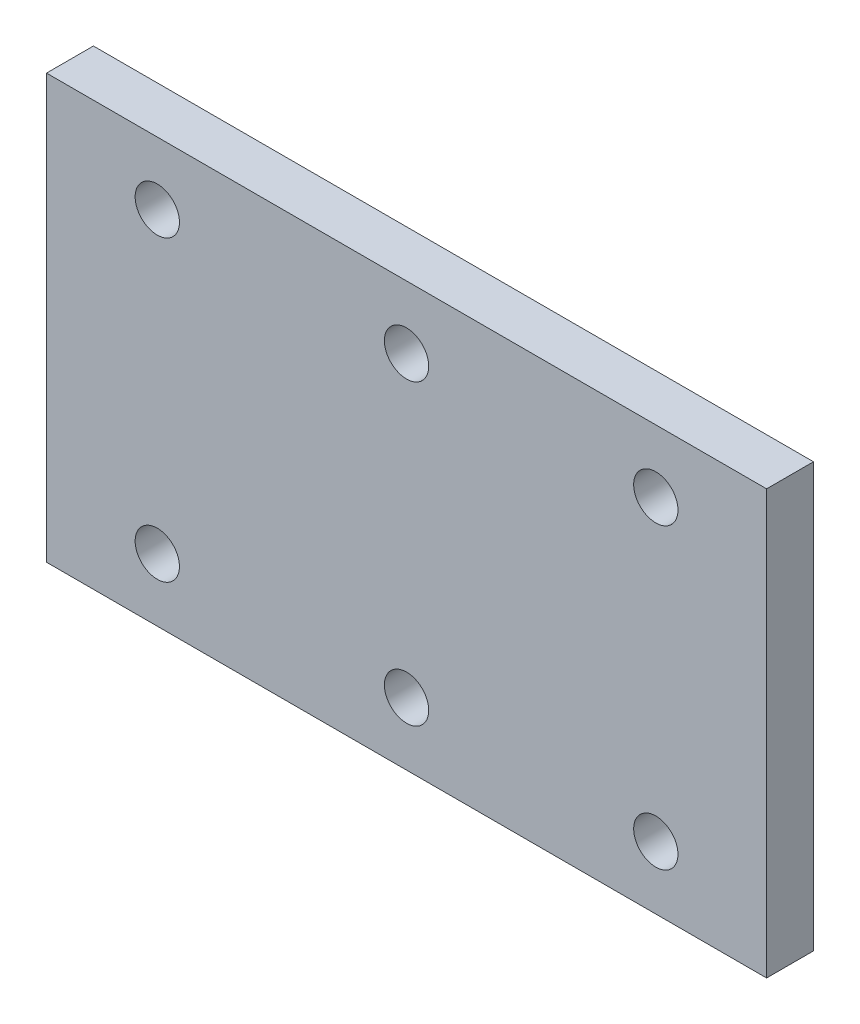
SolidWorks part; units mm, degrees
ref_plane "Front Plane" through (0, 0, 0) normal (0, 0, 1) x (1, 0, 0)
ref_plane "Top Plane" through (0, 0, 0) normal (0, 1, 0) x (1, 0, 0)
ref_plane "Right Plane" through (0, 0, 0) normal (1, 0, 0) x (0, 0, -1)
sketch "Sketch1" plane through (0, 0, 0) normal (0, 0, 1) x (1, 0, 0)
  line L1 (-48.75, 28.68) -> (48.75, 28.68)
  line L2 (-48.75, 28.68) -> (-48.75, -28.68)
  line L3 (-48.75, -28.68) -> (48.75, -28.68)
  line L4 (48.75, 28.68) -> (48.75, -28.68)
  line L5 (-48.75, 28.68) -> (48.75, -28.68) construction
  line L6 (-48.75, -28.68) -> (48.75, 28.68) construction
  point P0 (0, 0)
  dimension "D1" = 97.5
  dimension "D2" = 57.36
extrude "Boss-Extrude1" add sketch "Sketch1" along normal blind 6.35
sketch "Sketch2" plane through (0, 0, 6.35) normal (0, 0, 1) x (1, 0, 0)
  line L0 (-48.75, 28.68) -> (-48.75, -28.68) construction
  line L2 (48.75, 28.68) -> (-48.75, 28.68) construction
  line L3 (48.75, -28.68) -> (48.75, 28.68) construction
  line L5 (3.4925, 0) -> (-3.4925, 0) construction
  circle A0 centre (-33.75, 20.18) radius 3
  circle A1 centre (0, 20.18) radius 3
  circle A2 centre (33.75, 20.18) radius 3
  circle A6 centre (67.5, 20.18) radius 3 [skipped]
  circle A7 centre (101.25, 20.18) radius 3 [skipped]
  circle A8 centre (135, 20.18) radius 3 [skipped]
  circle A9 centre (33.75, -20.18) radius 3
  circle A10 centre (0, -20.18) radius 3
  circle A11 centre (-33.75, -20.18) radius 3
  dimension "D3" = 6
  dimension "D1" = 5.5
  dimension "D2" = 12
  dimension "D5" = 12
  dimension "D6" = 33.75
  dimension "D4" = 6
extrude "Cut-Extrude1" cut sketch "Sketch2" against normal through all
